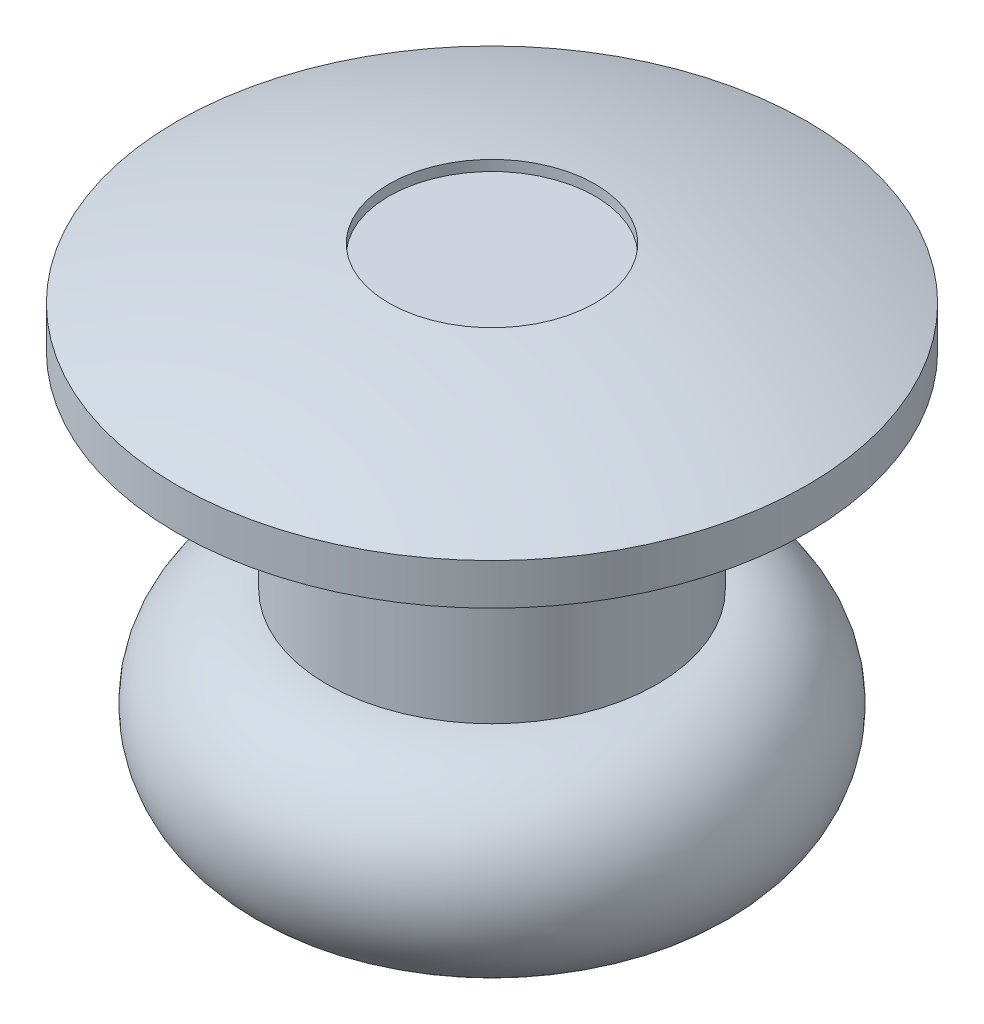
SolidWorks part; units mm, degrees
material "Aluminium"
ref_plane "Спереди" through (0, 0, 0) normal (0, 0, 1) x (1, 0, 0)
ref_plane "Сверху" through (0, 0, 0) normal (0, 1, 0) x (1, 0, 0)
ref_plane "Справа" through (0, 0, 0) normal (1, 0, 0) x (0, 0, -1)
sketch "Эскиз1" plane through (0, 0, 0) normal (0, 0, 1) x (1, 0, 0)
  line L0 (3.82, -1.2) -> (2, -1.2)
  line L1 (0, 0) -> (3.82, 0) construction
  line L2 (3.82, -0.7) -> (3.82, -1.2)
  line L3 (0, 0) -> (0, -6.1) construction
  line L4 (2, -1.2) -> (2, -3.7)
  line L5 (0, -0.2) -> (1.25, -0.2)
  line L6 (2, -6.1) -> (0, -6.1)
  line L7 (0, -0.2) -> (0, -6.1)
  line L8 (1.25, -0.2) -> (1.25, -0.0728)
  arc A0 (0, 0) -> (3.82, -0.7) centre (0, -10.7731) cw construction
  arc A1 (2, -3.7) -> (2, -6.1) centre (2, -4.9) cw
  arc A2 (1.25, -0.0728) -> (3.82, -0.7) centre (0, -10.7731) cw
  dimension "D1" = 7.64
  dimension "D4" = 4
  dimension "D6" = 1.2
  dimension "D7" = 2.5
  dimension "D2" = 1.2
  dimension "D3" = 0.5
  dimension "D5" = 2.5
  dimension "D8" = 0.2
revolve "Повернуть1" add sketch "Эскиз1" angle 360 about L7
sketch "Эскиз2" plane through (0, -1.2, 0) normal (0, -1, 0) x (-1, 0, 0)
  point P0 (0, 0)
